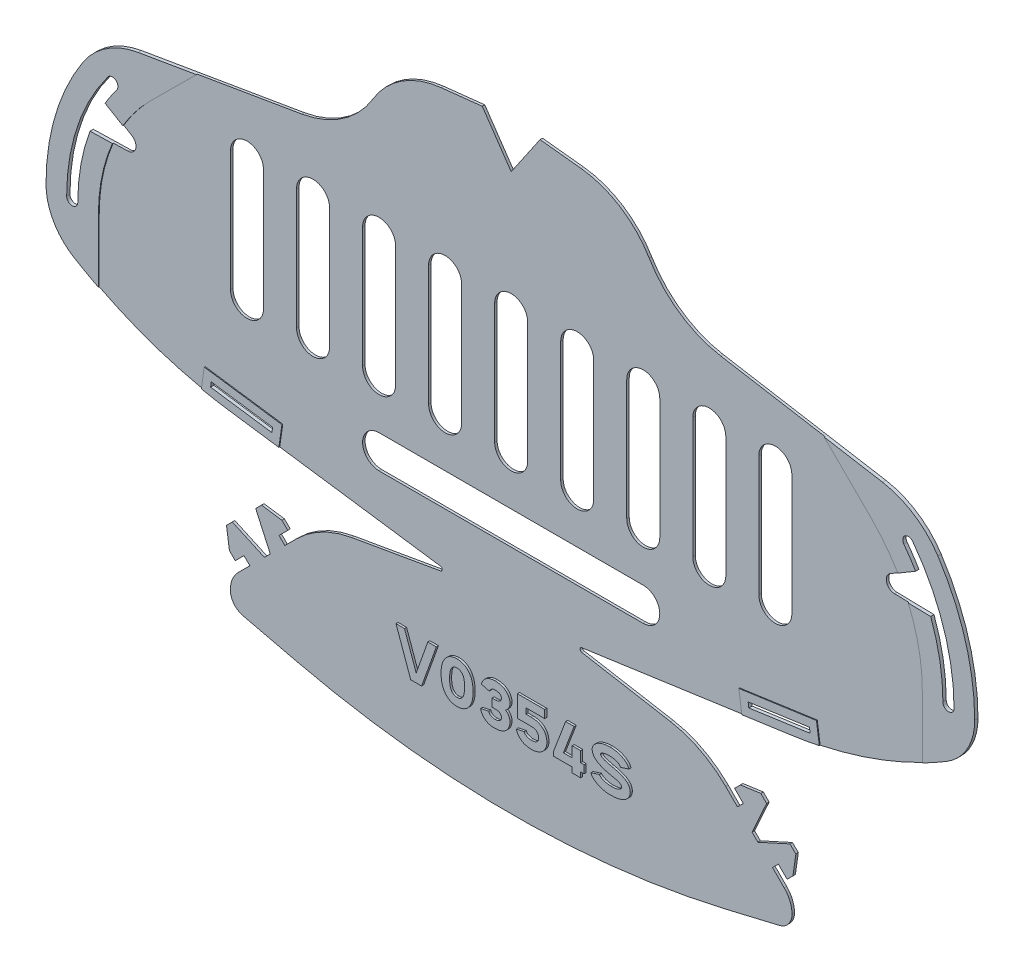
SolidWorks part; units mm, degrees
ref_plane "Front Plane" through (0, 0, 0) normal (0, 0, 1) x (1, 0, 0)
ref_plane "Top Plane" through (0, 0, 0) normal (0, 1, 0) x (1, 0, 0)
ref_plane "Right Plane" through (0, 0, 0) normal (1, 0, 0) x (0, 0, -1)
sketch "Sketch1" plane through (0, 0, 0) normal (0, 0, 1) x (1, 0, 0)
  line L0 (0, 0) -> (0, -145) construction
  line L1 (-14, -102) -> (14, -102) construction
  line L2 (-112.5, -69) -> (112.5, -69) construction
  line L3 (0, -10.2352) -> (-7, 0)
  line L4 (0, -10.2352) -> (7, 0)
  line L5 (7, 0) -> (16.9419, -1.0768)
  line L6 (-90.1804, -30.1909) -> (-50.7439, -23.5)
  line L7 (90.1804, -30.1909) -> (50.7439, -23.5)
  line L8 (-14, -102) -> (-68.2662, -94.2919)
  line L9 (-7, 0) -> (-16.9419, -1.0768)
  line L10 (14, -102) -> (68.2662, -94.2919)
  line L11 (-103.5977, -39) -> (-103.5977, -69) construction
  line L12 (-14, -102) -> (-38.6266, -106.305)
  line L13 (-52, -113.2546) -> (-54.8283, -116.0832)
  line L14 (52, -113.2546) -> (54.8283, -116.0832)
  line L15 (14, -102) -> (38.6266, -106.305)
  line L16 (-54.8283, -116.0832) -> (-56.2426, -114.669)
  line L17 (-56.2426, -114.669) -> (-54.1214, -112.5476)
  line L18 (-54.1214, -112.5476) -> (-55.5356, -111.1334)
  line L19 (-55.5356, -111.1334) -> (-60.4854, -110.4265)
  line L20 (-60.4854, -110.4265) -> (-68.9703, -118.9122)
  line L21 (-64.7275, -123.1546) -> (-63.3132, -124.5688)
  line L22 (-63.3132, -124.5688) -> (-66.1415, -127.3973)
  line L23 (-64.7275, -123.1546) -> (-66.8487, -125.2761)
  line L24 (-66.8487, -125.2761) -> (-68.263, -123.8619)
  line L25 (-68.9703, -118.9122) -> (-68.263, -123.8619)
  line L26 (68.9703, -118.9122) -> (68.263, -123.8619)
  line L27 (66.8487, -125.2761) -> (68.263, -123.8619)
  line L28 (64.7275, -123.1546) -> (66.8487, -125.2761)
  line L29 (63.3132, -124.5688) -> (66.1415, -127.3973)
  line L30 (64.7275, -123.1546) -> (63.3132, -124.5688)
  line L31 (60.4854, -110.4265) -> (68.9703, -118.9122)
  line L32 (55.5356, -111.1334) -> (60.4854, -110.4265)
  line L33 (54.1214, -112.5476) -> (55.5356, -111.1334)
  line L34 (56.2426, -114.669) -> (54.1214, -112.5476)
  line L35 (54.8283, -116.0832) -> (56.2426, -114.669)
  line L36 (-64.9691, -135.8852) -> (-52.4361, -138.8607)
  line L37 (64.9691, -135.8852) -> (52.4361, -138.8607)
  line L38 (-68.9703, -118.9122) -> (-64.7275, -123.1546) construction
  line L39 (-60.4854, -110.4265) -> (-56.2426, -114.669) construction
  arc A0 (-16.9419, -1.0768) -> (-33.4614, -11.6696) centre (-14.5729, -22.9489) ccw
  arc A1 (-33.4614, -11.6696) -> (-50.7439, -23.5) centre (-54.9257, 1.1478) cw
  arc A2 (-103.5977, -39) -> (-90.1804, -30.1909) centre (-86.8349, -49.9091) cw
  arc A3 (-112.5, -69) -> (-103.5977, -39) centre (-57.5, -69) cw
  arc A4 (112.5, -69) -> (103.5977, -39) centre (57.5, -69) ccw
  arc A5 (103.5977, -39) -> (90.1804, -30.1909) centre (86.8349, -49.9091) ccw
  arc A6 (16.9419, -1.0768) -> (33.4614, -11.6696) centre (14.5729, -22.9489) cw
  arc A7 (33.4614, -11.6696) -> (50.7439, -23.5) centre (54.9257, 1.1478) ccw
  arc A8 (-112.5, -69) -> (-105.7111, -81) centre (-98.5, -69) ccw
  arc A9 (-105.7111, -81) -> (-68.2662, -94.2919) centre (-54.2032, 4.7143) ccw
  arc A10 (112.5, -69) -> (105.7111, -81) centre (98.5, -69) cw
  arc A11 (105.7111, -81) -> (68.2662, -94.2919) centre (54.2032, 4.7143) cw
  arc A12 (-38.6266, -106.305) -> (-52, -113.2546) centre (-34.3216, -130.9315) ccw
  arc A13 (38.6266, -106.305) -> (52, -113.2546) centre (34.3216, -130.9315) cw
  arc A14 (-66.1415, -127.3973) -> (-68.0451, -131.9933) centre (-61.5451, -131.9933) ccw
  arc A15 (-68.0451, -131.9933) -> (-64.9691, -135.8852) centre (-64.0451, -131.9933) ccw
  arc A16 (68.0451, -131.9933) -> (64.9691, -135.8852) centre (64.0451, -131.9933) cw
  arc A17 (66.1415, -127.3973) -> (68.0451, -131.9933) centre (61.5451, -131.9933) cw
  arc A19 (-52.4361, -138.8607) -> (0, -145) centre (0, 82) ccw
  arc A20 (52.4361, -138.8607) -> (0, -145) centre (0, 82) cw
  point P8 (0, -102)
  point P11 (0, -69)
  dimension "D5" = 55
  dimension "D11" = 20
  dimension "D13" = 25
  dimension "D16" = 14
  dimension "D15" = 22
  dimension "D18" = 100
  dimension "D22" = 25
  dimension "D31" = 6.5
  dimension "D32" = 4
  dimension "D34" = 227
  dimension "D1" = 145
  dimension "D2" = 28
  dimension "D3" = 43
  dimension "D4" = 76
  dimension "D6" = 225
  dimension "D7" = 14
  dimension "D8" = 12.4
  dimension "D9" = 10
  dimension "D10" = 30
  dimension "D12" = 40
  dimension "D14" = 45.5
  dimension "D17" = 12
  dimension "D19" = 18
  dimension "D20" = 25
  dimension "D21" = 4
  dimension "D23" = 38
  dimension "D24" = 2
  dimension "D25" = 3
  dimension "D26" = 2
  dimension "D27" = 18
  dimension "D29" = 8
  dimension "D30" = 4
extrude "Main Shape" add sketch "Sketch1" along normal blind 0.6
sketch "Sketch2" plane through (0, 0, 0.6) normal (0, 0, 1) x (1, 0, 0)
  line L0 (0, -0.33) -> (0, 0.33) construction
  arc A0 (-96.42, -39.81) -> (-106.15, -69) centre (-57.5, -69) ccw construction
  arc A1 (-97.5, -39) -> (-107.5, -69) centre (-57.5, -69) ccw
  arc A2 (-95.34, -40.62) -> (-104.8, -69) centre (-57.5, -69) ccw
  arc A3 (-95.34, -40.62) -> (-97.5, -39) centre (-96.42, -39.81) ccw
  arc A4 (-107.5, -69) -> (-104.8, -69) centre (-106.15, -69) ccw
  arc A6 (-103.5977, -39) -> (-112.5, -69) centre (-57.5, -69) ccw construction
  arc A7 (96.42, -39.81) -> (106.15, -69) centre (57.5, -69) cw construction
  arc A8 (97.5, -39) -> (107.5, -69) centre (57.5, -69) cw
  arc A9 (95.34, -40.62) -> (104.8, -69) centre (57.5, -69) cw
  arc A10 (95.34, -40.62) -> (97.5, -39) centre (96.42, -39.81) cw
  arc A11 (107.5, -69) -> (104.8, -69) centre (106.15, -69) cw
  point P3 (-103.6534, -53.6155)
  point P19 (103.6534, -53.6155)
  dimension "D1" = 5
  dimension "D2" = 1.35
extrude "Elastic Attachment Points" cut sketch "Sketch2" against normal through all
sketch "Sketch7" plane through (0, 0, 0.6) normal (0, 0, 1) x (1, 0, 0)
  line L0 (-99.8, -69) -> (-99.8, -84.2853)
  line L1 (-87.321, -39) -> (-76.0466, -27.7929)
  line L2 (-50.7439, -23.5) -> (-90.1804, -30.1909) construction
  line L3 (-76.0466, -27.7929) -> (-90.1804, -30.1909)
  line L4 (0, -0.33) -> (0, 0.33) construction
  line L5 (76.0466, -27.7929) -> (90.1804, -30.1909)
  line L6 (87.321, -39) -> (76.0466, -27.7929)
  line L7 (99.8, -69) -> (99.8, -84.2853)
  arc A0 (-99.8, -69) -> (-87.321, -39) centre (-57.5, -69) cw
  arc A1 (-95.34, -40.62) -> (-104.8, -69) centre (-57.5, -69) ccw construction
  arc A2 (-105.7111, -81) -> (-68.2662, -94.2919) centre (-54.2032, 4.7143) ccw construction
  arc A3 (-112.5, -69) -> (-105.7111, -81) centre (-98.5, -69) ccw construction
  arc A4 (-103.5977, -39) -> (-112.5, -69) centre (-57.5, -69) ccw construction
  arc A5 (-90.1804, -30.1909) -> (-103.5977, -39) centre (-86.8349, -49.9091) ccw construction
  arc A6 (-105.7111, -81) -> (-99.8, -84.2853) centre (-54.2032, 4.7143) ccw
  arc A7 (-112.5, -69) -> (-105.7111, -81) centre (-98.5, -69) ccw
  arc A8 (-103.5977, -39) -> (-112.5, -69) centre (-57.5, -69) ccw
  arc A9 (-90.1804, -30.1909) -> (-103.5977, -39) centre (-86.8349, -49.9091) ccw
  arc A10 (90.1804, -30.1909) -> (103.5977, -39) centre (86.8349, -49.9091) cw
  arc A11 (103.5977, -39) -> (112.5, -69) centre (57.5, -69) cw
  arc A12 (112.5, -69) -> (105.7111, -81) centre (98.5, -69) cw
  arc A13 (105.7111, -81) -> (99.8, -84.2853) centre (54.2032, 4.7143) cw
  arc A14 (99.8, -69) -> (87.321, -39) centre (57.5, -69) ccw
  arc A15 (-107.5, -69) -> (-104.8, -69) centre (-106.15, -69) ccw construction
  arc A16 (-95.34, -40.62) -> (-97.5, -39) centre (-96.42, -39.81) ccw construction
  arc A17 (-97.5, -39) -> (-107.5, -69) centre (-57.5, -69) ccw construction
  arc A18 (-107.5, -69) -> (-104.8, -69) centre (-106.15, -69) ccw
  arc A19 (-95.34, -40.62) -> (-97.5, -39) centre (-96.42, -39.81) ccw
  arc A20 (-95.34, -40.62) -> (-104.8, -69) centre (-57.5, -69) ccw
  arc A21 (-97.5, -39) -> (-107.5, -69) centre (-57.5, -69) ccw
  arc A22 (104.8, -69) -> (107.5, -69) centre (106.15, -69) ccw construction
  arc A23 (97.5, -39) -> (95.34, -40.62) centre (96.42, -39.81) ccw construction
  arc A24 (104.8, -69) -> (95.34, -40.62) centre (57.5, -69) ccw construction
  arc A25 (107.5, -69) -> (97.5, -39) centre (57.5, -69) ccw construction
  arc A26 (104.8, -69) -> (107.5, -69) centre (106.15, -69) ccw
  arc A27 (97.5, -39) -> (95.34, -40.62) centre (96.42, -39.81) ccw
  arc A28 (104.8, -69) -> (95.34, -40.62) centre (57.5, -69) ccw
  arc A29 (107.5, -69) -> (97.5, -39) centre (57.5, -69) ccw
  dimension "D1" = 5
extrude "Reinforced Attachment Points" add sketch "Sketch7" along normal blind 0.2
sketch "Sketch6" plane through (0, 0, 0.6) normal (0, 0, 1) x (1, 0, 0)
  line L0 (-72.6274, -91.6524) -> (-57.7765, -93.7618)
  line L1 (-57.7765, -93.7618) -> (-57.6078, -92.5738)
  line L2 (-57.6078, -92.5738) -> (-72.4587, -90.4643)
  line L3 (-72.4587, -90.4643) -> (-72.6274, -91.6524)
  line L4 (-68.2662, -94.2919) -> (-14, -102) construction
  line L5 (-65.0332, -91.519) -> (-65.202, -92.7071) construction
  line L13 (0, -0.33) -> (0, 0.33) construction
  line L14 (65.0332, -91.519) -> (65.202, -92.7071) construction
  line L15 (72.6274, -91.6524) -> (72.4587, -90.4643)
  line L16 (57.6078, -92.5738) -> (57.7765, -93.7618)
  line L22 (57.6078, -92.5738) -> (72.4587, -90.4643)
  line L24 (72.6274, -91.6524) -> (57.7765, -93.7618)
  dimension "D1" = 2
  dimension "D2" = 15
  dimension "D3" = 52
  dimension "D4" = 1.2
extrude "Tab Slits" cut sketch "Sketch6" against normal through all
sketch "Sketch9" plane through (0, 0, 0.6) normal (0, 0, 1) x (1, 0, 0)
  line L4 (-57.7765, -93.7618) -> (-57.6078, -92.5738) construction
  line L5 (-72.6274, -91.6524) -> (-57.7765, -93.7618) construction
  line L6 (-72.4587, -90.4643) -> (-72.6274, -91.6524) construction
  line L7 (-57.6078, -92.5738) -> (-72.4587, -90.4643) construction
  line L12 (-57.7765, -93.7618) -> (-57.6078, -92.5738)
  line L13 (-72.6274, -91.6524) -> (-57.7765, -93.7618)
  line L14 (-72.4587, -90.4643) -> (-72.6274, -91.6524)
  line L15 (-57.6078, -92.5738) -> (-72.4587, -90.4643)
  line L16 (-56.0776, -96.0232) -> (-55.3464, -90.8749)
  line L17 (-68.2662, -94.2919) -> (-14, -102) construction
  line L18 (-55.3464, -90.8749) -> (-74.1575, -88.2029)
  line L19 (-74.1575, -88.2029) -> (-74.8573, -93.1295)
  line L20 (-68.2662, -94.2919) -> (-56.0776, -96.0232)
  line L21 (0, -0.33) -> (0, 0.33) construction
  line L22 (68.2662, -94.2919) -> (56.0776, -96.0232)
  line L23 (74.1575, -88.2029) -> (74.8573, -93.1295)
  line L24 (55.3464, -90.8749) -> (74.1575, -88.2029)
  line L25 (56.0776, -96.0232) -> (55.3464, -90.8749)
  line L26 (57.6078, -92.5738) -> (72.4587, -90.4643)
  line L27 (72.4587, -90.4643) -> (72.6274, -91.6524)
  line L28 (72.6274, -91.6524) -> (57.7765, -93.7618)
  line L29 (57.7765, -93.7618) -> (57.6078, -92.5738)
  arc A0 (-99.8, -84.2853) -> (-68.2662, -94.2919) centre (-54.2032, 4.7143) ccw construction
  arc A1 (-74.8573, -93.1295) -> (-68.2662, -94.2919) centre (-54.2032, 4.7143) ccw
  arc A2 (74.8573, -93.1295) -> (68.2662, -94.2919) centre (54.2032, 4.7143) cw
  dimension "D1" = 2
  dimension "D2" = 2
  dimension "D3" = 2
extrude "Reinforced Tab Slits" add sketch "Sketch9" along normal blind 0.2
sketch "Sketch11" plane through (0, 0, 0.6) normal (0, 0, 1) x (1, 0, 0)
  line L0 (-67.5562, -117.4979) -> (-59.7778, -121.0331)
  line L1 (-60.4854, -110.4265) -> (-68.9703, -118.9122) construction
  line L2 (-59.7778, -121.0331) -> (-58.3637, -119.6188)
  line L3 (-58.3637, -119.6188) -> (-61.8996, -111.8408)
  line L4 (-61.8996, -111.8408) -> (-67.5562, -117.4979)
  line L6 (-58.3637, -119.6188) -> (-54.8283, -116.0832) construction
  line L7 (-59.7778, -121.0331) -> (-63.3132, -124.5688) construction
  line L10 (0, -0.33) -> (0, 0.33) construction
  line L11 (59.7778, -121.0331) -> (63.3132, -124.5688) construction
  line L12 (58.3637, -119.6188) -> (54.8283, -116.0832) construction
  line L13 (61.8996, -111.8408) -> (67.5562, -117.4979)
  line L14 (58.3637, -119.6188) -> (61.8996, -111.8408)
  line L15 (59.7778, -121.0331) -> (58.3637, -119.6188)
  line L16 (67.5562, -117.4979) -> (59.7778, -121.0331)
  dimension "D1" = 2
  dimension "D2" = 2
  dimension "D3" = 5
extrude "Tab Flex Relief" cut sketch "Sketch11" against normal through all both and the other way through all
sketch "Sketch3" plane through (0, 0, 0.6) normal (0, 0, 1) x (1, 0, 0)
  line L3 (0, -10.2352) -> (0, -145) construction
  line L4 (-106.15, -69) -> (-96.42, -69) construction
  line L5 (-96.42, -69) -> (-96.42, -39.81) construction
  line L427 (0, -39.81) -> (0, -69) construction
  line L428 (4, -39.81) -> (4, -69)
  line L429 (-4, -39.81) -> (-4, -69)
  line L444 (-16, -39.81) -> (-16, -69) construction
  line L447 (-12, -39.81) -> (-12, -69)
  line L450 (-20, -39.81) -> (-20, -69)
  line L451 (-32, -39.81) -> (-32, -69) construction
  line L455 (-28, -39.81) -> (-28, -69)
  line L456 (-36, -39.81) -> (-36, -69)
  line L836 (-32, -85) -> (32, -85) construction
  line L837 (-32, -81) -> (32, -81)
  line L838 (-32, -89) -> (32, -89)
  line L839 (-64, -73) -> (64, -73) construction
  line L933 (-48, -39.81) -> (-48, -69) construction
  line L934 (-44, -39.81) -> (-44, -69)
  line L935 (-52, -39.81) -> (-52, -69)
  line L936 (-64, -39.81) -> (-64, -69) construction
  line L937 (-60, -39.81) -> (-60, -69)
  line L938 (-68, -39.81) -> (-68, -69)
  line L939 (16, -39.81) -> (16, -69) construction
  line L940 (12, -39.81) -> (12, -69)
  line L941 (20, -39.81) -> (20, -69)
  line L942 (32, -39.81) -> (32, -69) construction
  line L943 (28, -39.81) -> (28, -69)
  line L944 (36, -39.81) -> (36, -69)
  line L945 (48, -39.81) -> (48, -69) construction
  line L946 (44, -39.81) -> (44, -69)
  line L947 (52, -39.81) -> (52, -69)
  line L948 (64, -39.81) -> (64, -69) construction
  line L949 (60, -39.81) -> (60, -69)
  line L950 (68, -39.81) -> (68, -69)
  arc A2 (-52.4361, -138.8607) -> (52.4361, -138.8607) centre (0, 82) ccw construction
  arc A21 (4, -39.81) -> (-4, -39.81) centre (0, -39.81) ccw
  arc A22 (-4, -69) -> (4, -69) centre (0, -69) ccw
  arc A23 (-12, -39.81) -> (-20, -39.81) centre (-16, -39.81) ccw
  arc A24 (-20, -69) -> (-12, -69) centre (-16, -69) ccw
  arc A25 (-28, -39.81) -> (-36, -39.81) centre (-32, -39.81) ccw
  arc A26 (-36, -69) -> (-28, -69) centre (-32, -69) ccw
  arc A27 (-44, -39.81) -> (-52, -39.81) centre (-48, -39.81) ccw
  arc A28 (-52, -69) -> (-44, -69) centre (-48, -69) ccw
  arc A29 (-60, -39.81) -> (-68, -39.81) centre (-64, -39.81) ccw
  arc A30 (-68, -69) -> (-60, -69) centre (-64, -69) ccw
  arc A31 (12, -39.81) -> (20, -39.81) centre (16, -39.81) cw
  arc A32 (20, -69) -> (12, -69) centre (16, -69) cw
  arc A33 (28, -39.81) -> (36, -39.81) centre (32, -39.81) cw
  arc A34 (36, -69) -> (28, -69) centre (32, -69) cw
  arc A35 (44, -39.81) -> (52, -39.81) centre (48, -39.81) cw
  arc A36 (52, -69) -> (44, -69) centre (48, -69) cw
  arc A37 (60, -39.81) -> (68, -39.81) centre (64, -39.81) cw
  arc A38 (68, -69) -> (60, -69) centre (64, -69) cw
  arc A39 (-32, -81) -> (-32, -89) centre (-32, -85) ccw
  arc A40 (32, -89) -> (32, -81) centre (32, -85) ccw
  point P3 (-16, -54.405)
  point P18 (-32, -54.405)
  point P30 (-48, -54.405)
  point P37 (-64, -54.405)
  point P43 (16, -54.405)
  point P50 (32, -54.405)
  point P57 (48, -54.405)
  point P64 (64, -54.405)
  point P71 (0, -85)
  point P414 (0, -54.405)
  dimension "D5" = 8
  dimension "D1" = 8
  dimension "D2" = 5
  dimension "D3" = 8
  dimension "D4" = 8
extrude "Breathing Slits" cut sketch "Sketch3" against normal through all
sketch "Sketch8" plane through (0, 0, 0.6) normal (0, 0, 1) x (1, 0, 0)
  line L0 (-67.0266, -128.5) -> (67.0266, -128.5) construction
  line L1 (0, -10.2352) -> (0, -145) construction
  arc A0 (-52.4361, -138.8607) -> (52.4361, -138.8607) centre (0, 82) ccw construction
  arc A1 (-66.1415, -127.3973) -> (-68.0451, -131.9933) centre (-61.5451, -131.9933) ccw construction
  text T0 "<b>V0354S</b>\r\n" font "Double Porter 3" height 10
  point P9 (0, -128.5)
  dimension "D2" = 16.5
extrude "Version Number" add sketch "Sketch8" along normal blind 0.5
fillet "Fillet1" radius 0.5 2 edges at (-14, -102, 0.3) (14, -102, 0.3)
sketch "Sketch12" plane through (0, 0, 0.8) normal (0, 0, 1) x (1, 0, 0)
  line L0 (-98.1829, -44.8713) -> (-91.8731, -48.6136)
  line L1 (-98.1829, -44.8713) -> (-89.3972, -30.058) construction
  line L2 (-76.0466, -27.7929) -> (-90.1804, -30.1909) construction
  line L3 (-101.8445, -52.5422) -> (-92.8469, -52.3333)
  line L4 (0, -0.33) -> (0, 0.33) construction
  line L5 (98.1829, -44.8713) -> (89.3972, -30.058) construction
  line L6 (101.8445, -52.5422) -> (92.8469, -52.3333)
  line L7 (98.1829, -44.8713) -> (91.8731, -48.6136)
  arc A0 (-95.34, -40.62) -> (-104.8, -69) centre (-57.5, -69) ccw construction
  arc A1 (-92.8469, -52.3333) -> (-91.8731, -48.6136) centre (-92.8933, -50.3338) ccw
  arc A2 (-98.1829, -44.8713) -> (-101.8445, -52.5422) centre (-57.5, -69) ccw
  arc A3 (98.1829, -44.8713) -> (101.8445, -52.5422) centre (57.5, -69) cw
  arc A4 (92.8469, -52.3333) -> (91.8731, -48.6136) centre (92.8933, -50.3338) cw
  dimension "D4" = 2
  dimension "D1" = 24.1287
  dimension "D2" = 8.5
  dimension "D3" = 9
extrude "Cut-Extrude1" cut sketch "Sketch12" against normal through all both and the other way through all
